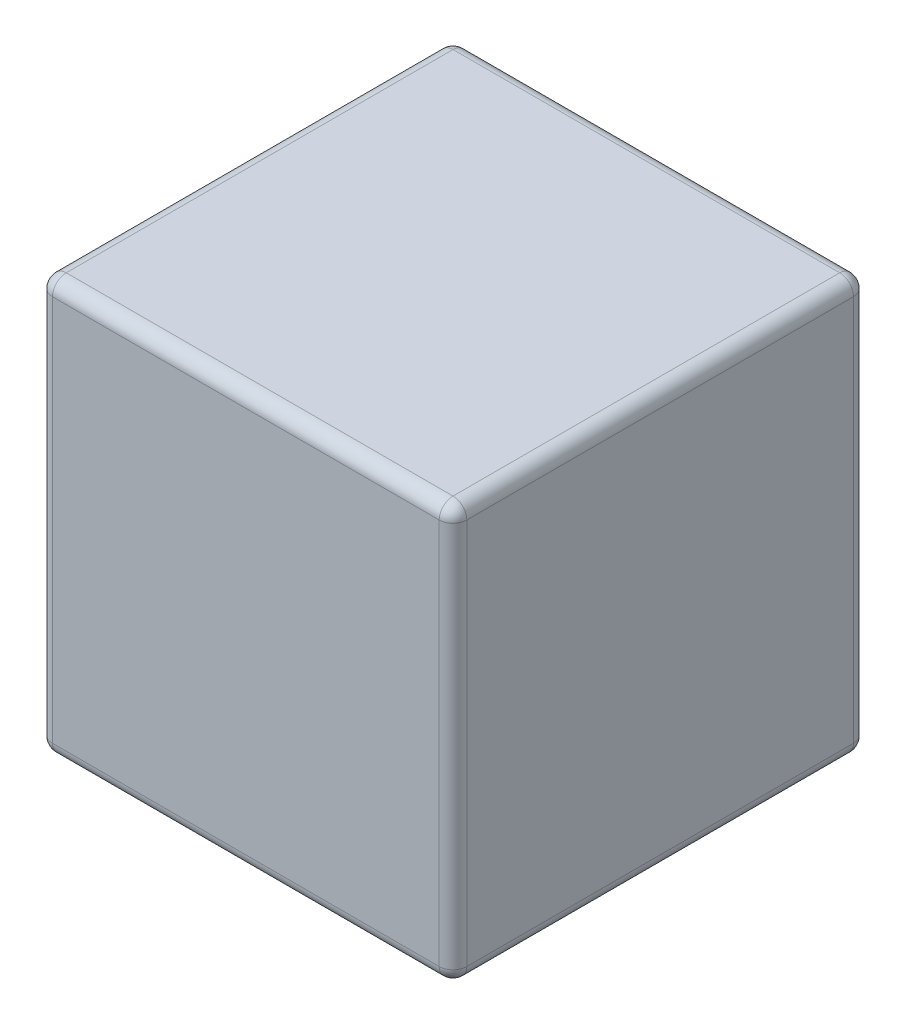
SolidWorks part; units mm, degrees
material "PVC rigide"
ref_plane "Plan de face" through (0, 0, 0) normal (0, 0, 1) x (1, 0, 0)
ref_plane "Plan de dessus" through (0, 0, 0) normal (0, 1, 0) x (1, 0, 0)
ref_plane "Plan de droite" through (0, 0, 0) normal (1, 0, 0) x (0, 0, -1)
sketch "Esquisse1" plane through (0, 0, 0) normal (0, 0, 1) x (1, 0, 0)
  line L1 (-15, 15) -> (15, 15)
  line L2 (-15, 15) -> (-15, -15)
  line L3 (-15, -15) -> (15, -15)
  line L4 (15, 15) -> (15, -15)
  line L5 (-15, 15) -> (15, -15) construction
  line L6 (-15, -15) -> (15, 15) construction
  point P0 (0, 0)
  dimension "D1" = 30
  dimension "D2" = 30
extrude "Boss.-Extru.1" add sketch "Esquisse1" along normal blind 30
fillet "Congé1" radius 1 12 edges at (0, -15, 0) (-15, -15, 15) (-15, 0, 0) (0, -15, 30) (-15, 0, 30) (15, -15, 15) (15, 0, 30) (15, 0, 0) (15, 15, 15) (0, 15, 30) (-15, 15, 15) (0, 15, 0)
